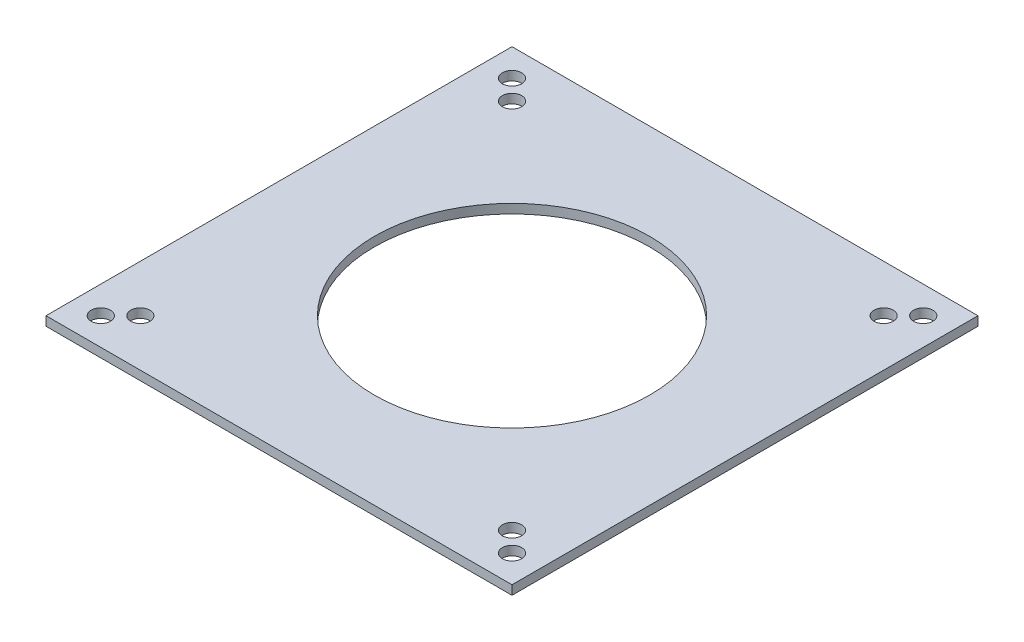
SolidWorks part; units mm, degrees
ref_plane "Plan de face" through (0, 0, 0) normal (0, 0, 1) x (1, 0, 0)
ref_plane "Plan de dessus" through (0, 0, 0) normal (0, 1, 0) x (1, 0, 0)
ref_plane "Plan de droite" through (0, 0, 0) normal (1, 0, 0) x (0, 0, -1)
sketch "Sketch1" plane through (0, 0, 0) normal (0, 1, 0) x (1, 0, 0)
  line L1 (-50.8, -50.8) -> (50.8, -50.8)
  line L2 (-50.8, -50.8) -> (-50.8, 50.8)
  line L3 (-50.8, 50.8) -> (50.8, 50.8)
  line L4 (50.8, -50.8) -> (50.8, 50.8)
  line L5 (-50.8, -50.8) -> (50.8, 50.8) construction
  line L6 (-50.8, 50.8) -> (50.8, -50.8) construction
  line L7 (-40.513, -40.513) -> (40.513, -40.513) construction
  line L8 (-40.513, -40.513) -> (-40.513, 40.513) construction
  line L9 (-40.513, 40.513) -> (40.513, 40.513) construction
  line L10 (40.513, -40.513) -> (40.513, 40.513) construction
  line L11 (-40.513, -40.513) -> (40.513, 40.513) construction
  line L12 (-40.513, 40.513) -> (40.513, -40.513) construction
  line L13 (-44.831, -44.831) -> (44.831, -44.831) construction
  line L14 (-44.831, -44.831) -> (-44.831, 44.831) construction
  line L15 (-44.831, 44.831) -> (44.831, 44.831) construction
  line L16 (44.831, -44.831) -> (44.831, 44.831) construction
  line L17 (-44.831, -44.831) -> (44.831, 44.831) construction
  line L18 (-44.831, 44.831) -> (44.831, -44.831) construction
  circle A0 centre (-44.831, 44.831) radius 2.1
  circle A1 centre (-40.513, 40.513) radius 2.1
  circle A2 centre (44.831, 44.831) radius 2.1
  circle A3 centre (40.513, 40.513) radius 2.1
  circle A4 centre (44.831, -44.831) radius 2.1
  circle A5 centre (40.513, -40.513) radius 2.1
  circle A6 centre (-40.513, -40.513) radius 2.1
  circle A7 centre (-44.831, -44.831) radius 2.1
  circle A8 centre (0, 0) radius 30
  point P0 (0, 0)
  point P5 (0, 0)
  point P11 (0, 0)
  dimension "D4" = 4.2
  dimension "D5" = 4.2
  dimension "D6" = 4.2
  dimension "D7" = 4.2
  dimension "D8" = 4.2
  dimension "D9" = 4.2
  dimension "D10" = 4.2
  dimension "D11" = 4.2
  dimension "D12" = 60
  dimension "D1" = 101.6
  dimension "D2" = 81.026
  dimension "D3" = 89.662
extrude "Boss-Extrude1" add sketch "Sketch1" along normal blind 2
